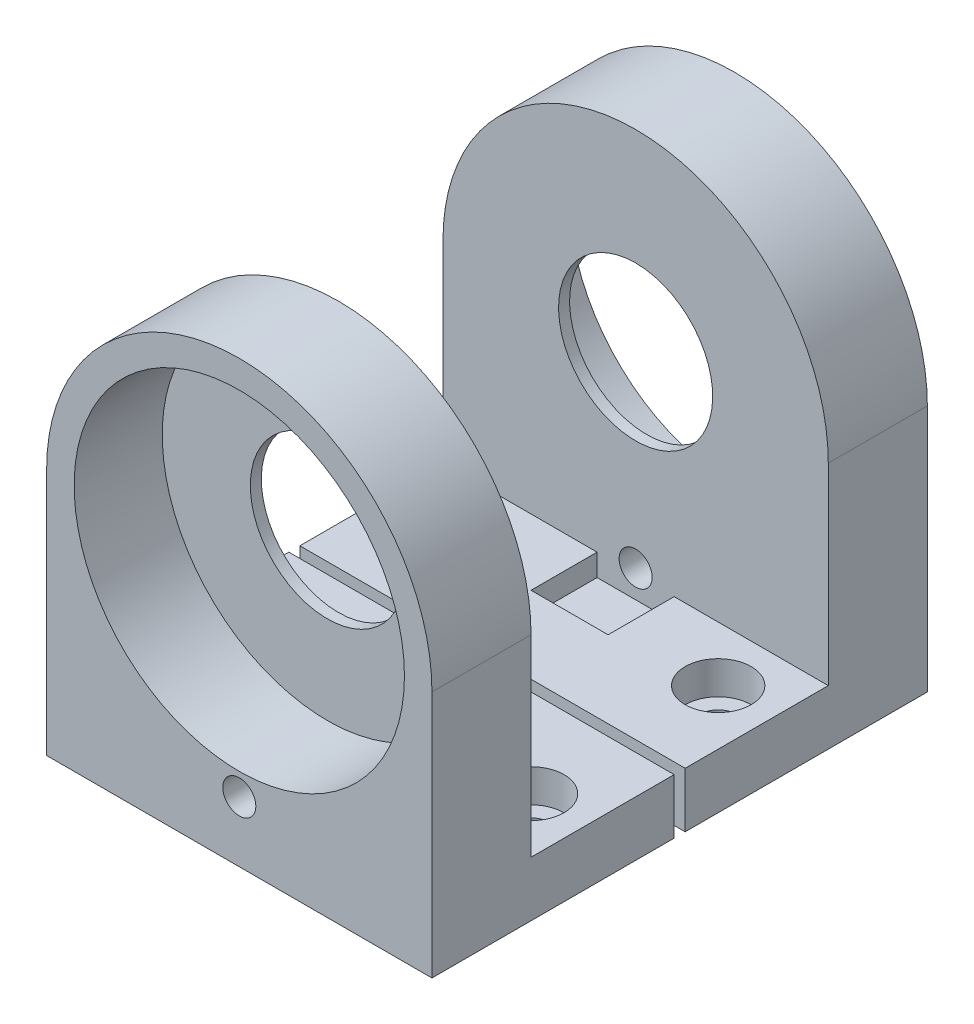
SolidWorks part; units mm, degrees
other "标注1"
sketch "草图5" plane through (-20, 40, 22.5) normal (-0.1295, 0.131, 0.9829) x (0.9907, 0.0594, 0.1226)
other "标注2"
sketch "草图13" plane through (-17.5, 0, -22.5) normal (-0.0964, -0.0078, -0.9953) x (0.9949, 0.0275, -0.0965)
other "标注3"
sketch "草图14" plane through (-17.5, 0, -22.5) normal (-0.0964, -0.0078, -0.9953) x (0.9949, 0.0275, -0.0965)
ref_plane "前视基准面" through (0, 0, 0) normal (0, 0, 1) x (1, 0, 0)
ref_plane "上视基准面" through (0, 0, 0) normal (0, 1, 0) x (1, 0, 0)
ref_plane "右视基准面" through (0, 0, 0) normal (1, 0, 0) x (0, 0, -1)
sketch "草图1" plane through (0, 0, 0) normal (1, 0, 0) x (0, 0, -1)
  line L0 (22.5, 0) -> (-22.5, 0)
  line L1 (-22.5, 0) -> (-22.5, 40)
  line L2 (-22.5, 40) -> (-13.5, 40)
  line L3 (-13.5, 40) -> (-13.5, 5)
  line L4 (-13.5, 5) -> (13.5, 5)
  line L5 (0, 5) -> (0, 0) construction
  line L6 (13.5, 40) -> (13.5, 5)
  line L7 (22.5, 40) -> (13.5, 40)
  line L8 (22.5, 0) -> (22.5, 40)
  dimension "D1" = 45
  dimension "D2" = 40
  dimension "D3" = 5
  dimension "D4" = 27
extrude "凸台-拉伸1" add sketch "草图1" along normal mid plane 35
sketch "草图2" plane through (0, 0, 22.5) normal (0, 0, 1) x (1, 0, 0)
  line L0 (17.5, 40) -> (17.5, 0) construction
  line L1 (17.5, 40) -> (-17.5, 40) construction
  line L2 (-17.5, 40) -> (-17.5, 0) construction
  line L3 (17.5, 40) -> (17.5, 10.3175)
  line L4 (17.5, 40) -> (-17.5, 40)
  line L5 (-17.5, 40) -> (-17.5, 22.5)
  arc A1 (17.5, 22.5) -> (-17.5, 22.5) centre (0, 22.5) ccw
  line M2 (-17.5, 40) -> (-17.5, 0)
  line M5 (17.5, 40) -> (-17.5, 40)
  dimension "D1" = 35
extrude "切除-拉伸1" cut sketch "草图2" against normal through all both and the other way through all contours A1 L4 M2 | A1 L3 M5
sketch "草图6" plane through (0, 5, 0) normal (0, 1, 0) x (1, 0, 0)
  line L0 (-17.5, 0) -> (17.5, 0) construction
  line L1 (-17.5, 13.5) -> (-17.5, -13.5) construction
  line L2 (17.5, 13.5) -> (17.5, -13.5) construction
  line L3 (0, 13.5) -> (0, -13.5) construction
  line L4 (17.5, 13.5) -> (-17.5, 13.5) construction
  line L5 (17.5, -13.5) -> (-17.5, -13.5) construction
  circle A0 centre (-12.5, 8.5) radius 1.55
  circle A1 centre (12.5, 8.5) radius 1.55
  circle A2 centre (12.5, -8.5) radius 1.55
  circle A3 centre (-12.5, -8.5) radius 1.55
  dimension "D1" = 3.1
  dimension "D2" = 5
  dimension "D3" = 5
extrude "切除-拉伸4" cut sketch "草图6" against normal through all
sketch "草图7" plane through (0, 0, 22.5) normal (0, 0, 1) x (1, 0, 0)
  circle A0 centre (0, 22.5) radius 15
  dimension "D1" = 30
extrude "切除-拉伸5" cut sketch "草图7" against normal blind 8
sketch "草图8" plane through (0, 0, 14.5) normal (0, 0, 1) x (1, 0, 0)
  circle A0 centre (0, 22.5) radius 7
  dimension "D1" = 14
extrude "切除-拉伸6" cut sketch "草图8" against normal blind 2
mirror "镜向1" about plane through (0, 0, 0) normal (0, 0, 1) of "切除-拉伸5", "切除-拉伸6"
sketch "草图9" plane through (0, 0, -22.5) normal (0, 0, -1) x (-1, 0, 0)
  line L0 (-17.5, 0) -> (-17.5, 22.5) construction
  circle A0 centre (0, 5.5) radius 1.5
  circle A1 centre (0, 22.5) radius 15 construction
  dimension "D1" = 17.5
  dimension "D2" = 17
extrude "切除-拉伸7" cut sketch "草图9" against normal blind 14
sketch "草图10" plane through (0, 5, 0) normal (0, 1, 0) x (1, 0, 0)
  line L0 (-1.4142, 13.5) -> (-17.5, 13.5) construction
  line L1 (-3.5, 13.5) -> (3.5, 13.5)
  line L2 (-3.5, 13.5) -> (-3.5, 7.5)
  line L3 (-3.5, 7.5) -> (3.5, 7.5)
  line L4 (3.5, 13.5) -> (3.5, 7.5)
  line L6 (17.5, 13.5) -> (17.5, -13.5) construction
  line L7 (-17.5, 13.5) -> (-17.5, -13.5) construction
  dimension "D1" = 14
  dimension "D2" = 14
extrude "切除-拉伸8" cut sketch "草图10" against normal blind 2
mirror "镜向2" about plane through (0, 0, 0) normal (0, 0, 1) of "切除-拉伸8", "切除-拉伸7"
sketch "草图15" plane through (0, 5, 0) normal (0, 1, 0) x (1, 0, 0)
  line L0 (-17.5, 0) -> (17.5, 0) construction
  line L1 (-17.5, 13.5) -> (-17.5, -13.5) construction
  line L2 (17.5, 13.5) -> (17.5, -13.5) construction
  line L4 (-17.5, 0.5) -> (17.5, 0.5)
  line L5 (-17.5, 0.5) -> (-17.5, -0.5)
  line L6 (-17.5, -0.5) -> (17.5, -0.5)
  line L7 (17.5, 0.5) -> (17.5, -0.5)
  dimension "D1" = 1
  dimension "D2" = 0.5
extrude "切除-拉伸9" cut sketch "草图15" against normal blind 10
sketch "草图16" plane through (0, 5, 0) normal (0, 1, 0) x (1, 0, 0)
  circle A0 centre (-12.5, 8.5) radius 3
  circle A1 centre (12.5, 8.5) radius 3
  circle A2 centre (12.5, -8.5) radius 3
  circle A3 centre (-12.5, -8.5) radius 3
  dimension "D1" = 6
extrude "切除-拉伸10" cut sketch "草图16" against normal blind 3
